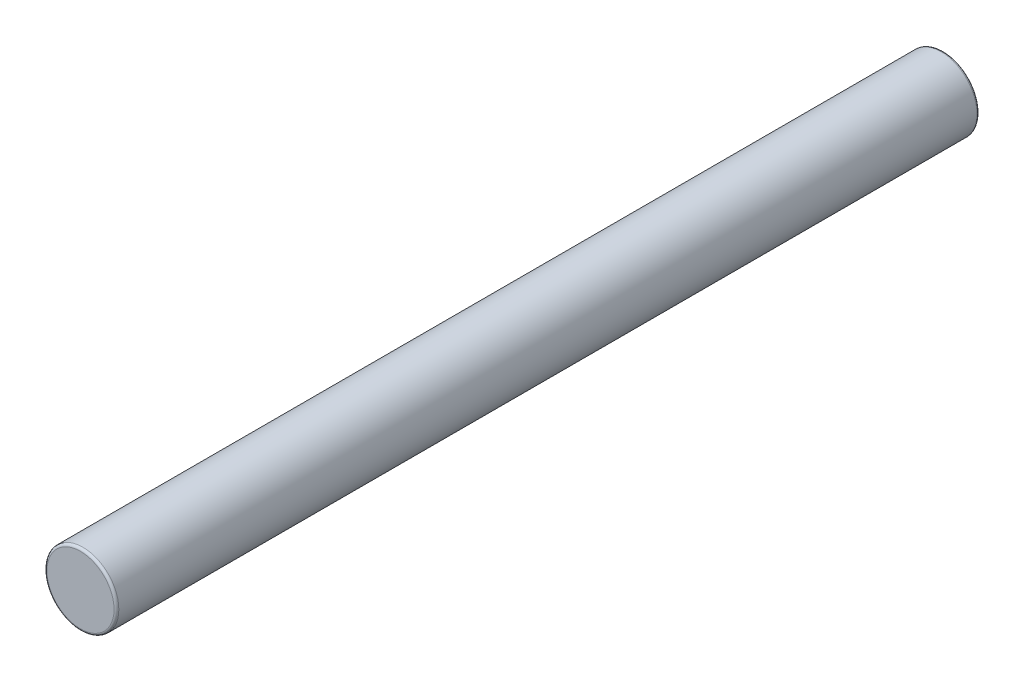
SolidWorks part; units mm, degrees
ref_plane "Front Plane" through (0, 0, 0) normal (0, 0, 1) x (1, 0, 0)
ref_plane "Top Plane" through (0, 0, 0) normal (0, 1, 0) x (1, 0, 0)
ref_plane "Right Plane" through (0, 0, 0) normal (1, 0, 0) x (0, 0, -1)
sketch "Sketch1" plane through (0, 0, 0) normal (0, 0, 1) x (1, 0, 0)
  circle A0 centre (0, 0) radius 1.5
  dimension "D1" = 3
extrude "Extrude1" add sketch "Sketch1" along normal blind 36
fillet "Fillet1" radius 0.1 2 edges at (1.5, 0, 0) (1.5, 0, 36)
